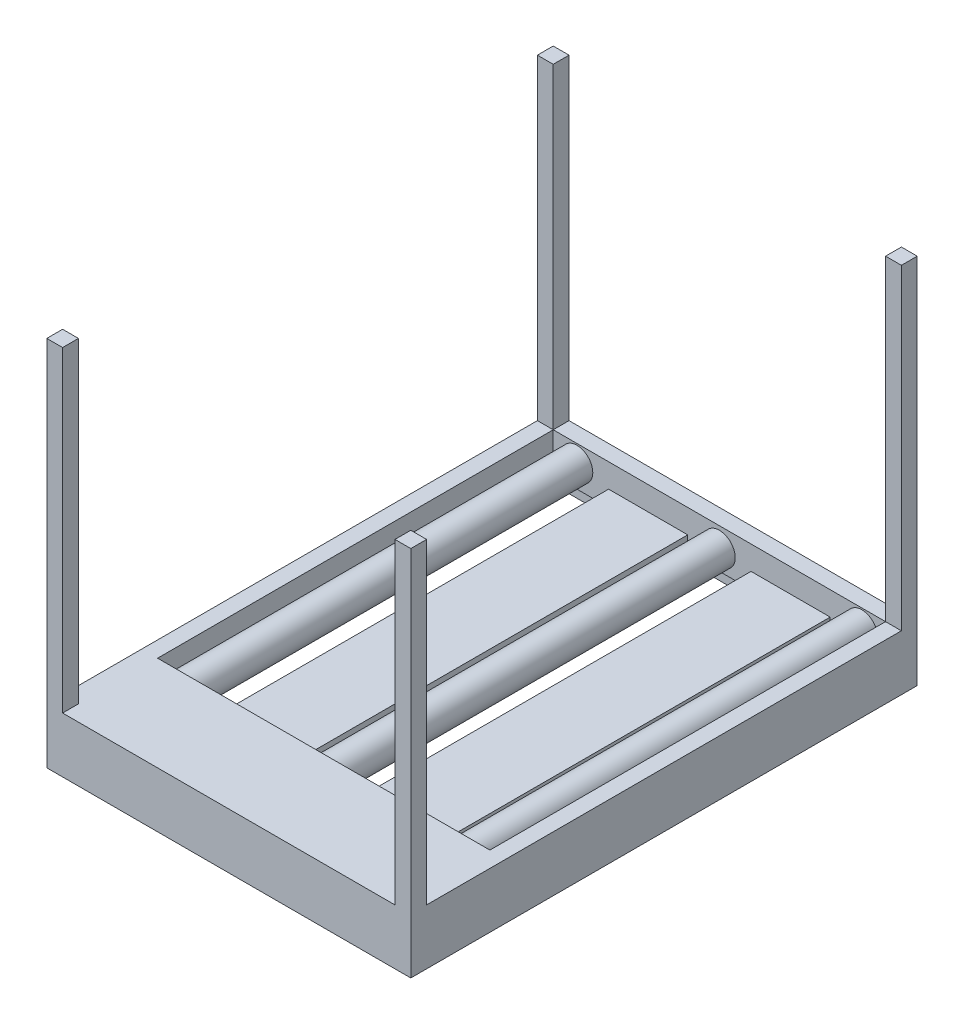
SolidWorks part; units mm, degrees
ref_plane "Front Plane" through (0, 0, 0) normal (0, 0, 1) x (1, 0, 0)
ref_plane "Top Plane" through (0, 0, 0) normal (0, 1, 0) x (1, 0, 0)
ref_plane "Right Plane" through (0, 0, 0) normal (1, 0, 0) x (0, 0, -1)
sketch "Sketch1" plane through (0, 0, 0) normal (0, 0, 1) x (1, 0, 0)
  line L0 (400, 0) -> (400, -50)
  line L1 (0, 0) -> (250, 0)
  line L2 (0, 0) -> (0, -50)
  line L3 (0, -50) -> (250, -50)
  line L4 (250, 0) -> (250, -50)
  line L6 (250, 50) -> (250, -50)
  line L8 (400, 50) -> (400, -50)
  line L9 (400, 0) -> (650, 0)
  line L10 (650, 0) -> (650, -50)
  line L11 (400, -50) -> (650, -50)
  line L12 (650, 50) -> (650, -50)
  line L14 (800, 50) -> (800, -50)
  line L16 (800, 0) -> (800, -50)
  line L17 (800, 0) -> (1050, 0)
  line L18 (1050, 0) -> (1050, -50)
  line L19 (800, -50) -> (1050, -50)
  line L20 (1050, 50) -> (1050, -50)
  line L24 (1200, 50) -> (1200, -50) [skipped]
  dimension "D1" = 250
  dimension "D2" = 50
  dimension "D3" = 150
  dimension "D4" = 100
  dimension "D5" = 3
extrude "Boss-Extrude1" add sketch "Sketch1" along normal blind 1500 contours L14 L19 L18 L17 L16 | L0 L11 L10 L9 | L4 L1 L2 L3
sketch "Sketch2" plane through (0, 0, 0) normal (0, 1, 0) x (1, 0, 0)
  line L0 (1100, -1550) -> (1100, 50)
  line L1 (1050, -1500) -> (0, -1500)
  line L2 (1050, -1500) -> (1050, 0)
  line L3 (1050, 0) -> (0, 0)
  line L4 (0, -1500) -> (0, 0)
  line L5 (1100, 50) -> (-50, 50)
  line L6 (-50, -1550) -> (-50, 50)
  line L7 (1100, -1550) -> (-50, -1550)
  dimension "D1" = 50
extrude "Boss-Extrude2" add sketch "Sketch2" against normal blind 75 and the other way blind 50 contours L2 L1 L4 L3 | L0 L5 L6 L7
sketch "Sketch3" plane through (0, 50, 0) normal (0, 1, 0) x (1, 0, 0)
  line L0 (1100, 50) -> (-50, 50) construction
  line L1 (-50, 50) -> (0, 50)
  line L2 (-50, 50) -> (-50, 0)
  line L3 (-50, 0) -> (0, 0)
  line L4 (0, 50) -> (0, 0)
  line L5 (1100, 50) -> (1050, 50)
  line L6 (1100, 50) -> (1100, 0)
  line L7 (1100, 0) -> (1050, 0)
  line L8 (1050, 50) -> (1050, 0)
  line L9 (1100, -1550) -> (1100, 50) construction
  line L11 (-50, -1550) -> (0, -1550)
  line L12 (-50, -1550) -> (-50, -1500)
  line L13 (-50, -1500) -> (0, -1500)
  line L14 (0, -1550) -> (0, -1500)
  line L15 (1100, -1550) -> (1050, -1550)
  line L16 (1100, -1550) -> (1100, -1500)
  line L17 (1100, -1500) -> (1050, -1500)
  line L18 (1050, -1550) -> (1050, -1500)
extrude "Boss-Extrude3" add sketch "Sketch3" along normal blind 1000
sketch "Sketch4" plane through (0, -50, 0) normal (0, -1, 0) x (1, 0, 0)
  line L1 (1050, 0) -> (0, 0)
  line L2 (1050, 0) -> (1050, 1500)
  line L3 (1050, 1500) -> (0, 1500)
  line L4 (0, 0) -> (0, 1500)
extrude "Cut-Extrude1" cut sketch "Sketch4" against normal blind 134
sketch "Sketch5" plane through (0, 0, 0) normal (0, 0, 1) x (1, 0, 0)
  line L0 (525, -75) -> (525, 50)
  line L1 (1050, -75) -> (0, -75) construction
  line L2 (1050, 50) -> (0, 50) construction
  line L3 (625, -25) -> (875, -25)
  line L4 (425, -75) -> (175, -75)
  line L5 (425, -75) -> (425, -25)
  line L6 (425, -25) -> (175, -25)
  line L7 (175, -75) -> (175, -25)
  line L8 (875, -75) -> (875, -25)
  line L9 (625, -75) -> (875, -75)
  line L10 (625, -75) -> (625, -25)
  circle A0 centre (525, -12.5) radius 50
  circle A1 centre (75, -5) radius 50
  circle A2 centre (975, -5) radius 50
  line M15 (0, -75) -> (1050, -75)
  dimension "D1" = 250
  dimension "D3" = 100
  dimension "D2" = 100
  dimension "D4" = 50
extrude "Boss-Extrude4" add sketch "Sketch5" along normal blind 1500 contours L0 A0 | L0 A0 | L7 L5 L6 M15 | L10 L8 L3 M15 | A2 | A1
sketch "Sketch6" plane through (0, 0, 0) normal (0, 1, 0) x (1, 0, 0)
  line L0 (1050, -1500) -> (875, -1500) construction
  circle A0 centre (975, -1425) radius 25
  circle A1 centre (975, -1275) radius 25
  circle A2 centre (975, -1125) radius 25
  circle A3 centre (975, -975) radius 25
  circle A4 centre (975, -825) radius 25
  circle A5 centre (975, -675) radius 25
  circle A6 centre (975, -525) radius 25
  circle A7 centre (975, -375) radius 25
  circle A8 centre (975, -225) radius 25
  circle A9 centre (975, -75) radius 25
  circle A10 centre (525, -1425) radius 25
  circle A11 centre (75, -1425) radius 25
  circle A12 centre (525, -1275) radius 25
  circle A13 centre (75, -1275) radius 25
  circle A14 centre (525, -1125) radius 25
  circle A15 centre (75, -1125) radius 25
  circle A16 centre (525, -975) radius 25
  circle A17 centre (75, -975) radius 25
  circle A18 centre (525, -825) radius 25
  circle A19 centre (75, -825) radius 25
  circle A20 centre (525, -675) radius 25
  circle A21 centre (75, -675) radius 25
  circle A22 centre (525, -525) radius 25
  circle A23 centre (75, -525) radius 25
  circle A24 centre (525, -375) radius 25
  circle A25 centre (75, -375) radius 25
  circle A26 centre (525, -225) radius 25
  circle A27 centre (75, -225) radius 25
  circle A28 centre (525, -75) radius 25
  circle A29 centre (75, -75) radius 25
  dimension "D1" = 50
  dimension "D2" = 75
  dimension "D3" = 10
  dimension "D4" = 3
  dimension "D5" = 10
extrude "Cut-Extrude3" cut sketch "Sketch6" against normal blind 75
sketch "Sketch7" plane through (-50, 0, 0) normal (-1, 0, 0) x (0, 0, 1)
  line L0 (1550, -75) -> (-50, -75) construction
  line L1 (1500, 50) -> (1250, 50)
  line L2 (1500, 50) -> (1500, -75)
  line L3 (1500, -75) -> (1250, -75)
  line L4 (1250, 50) -> (1250, -75)
  dimension "D1" = 250
extrude "Boss-Extrude5" add sketch "Sketch7" against normal blind 1150
sketch "Sketch8" plane through (0, -75, 0) normal (0, -1, 0) x (1, 0, 0)
  line L0 (-25, 1525) -> (-25, -25)
  line L1 (-50, 1550) -> (1100, 1550)
  line L2 (-50, 1550) -> (-50, -50)
  line L3 (-50, -50) -> (1100, -50)
  line L4 (1100, 1550) -> (1100, -50)
  line L5 (-25, -25) -> (1075, -25)
  line L6 (1075, 1525) -> (1075, -25)
  line L7 (-25, 1525) -> (1075, 1525)
  dimension "D1" = 25
extrude "Boss-Extrude6" add sketch "Sketch8" along normal blind 50
